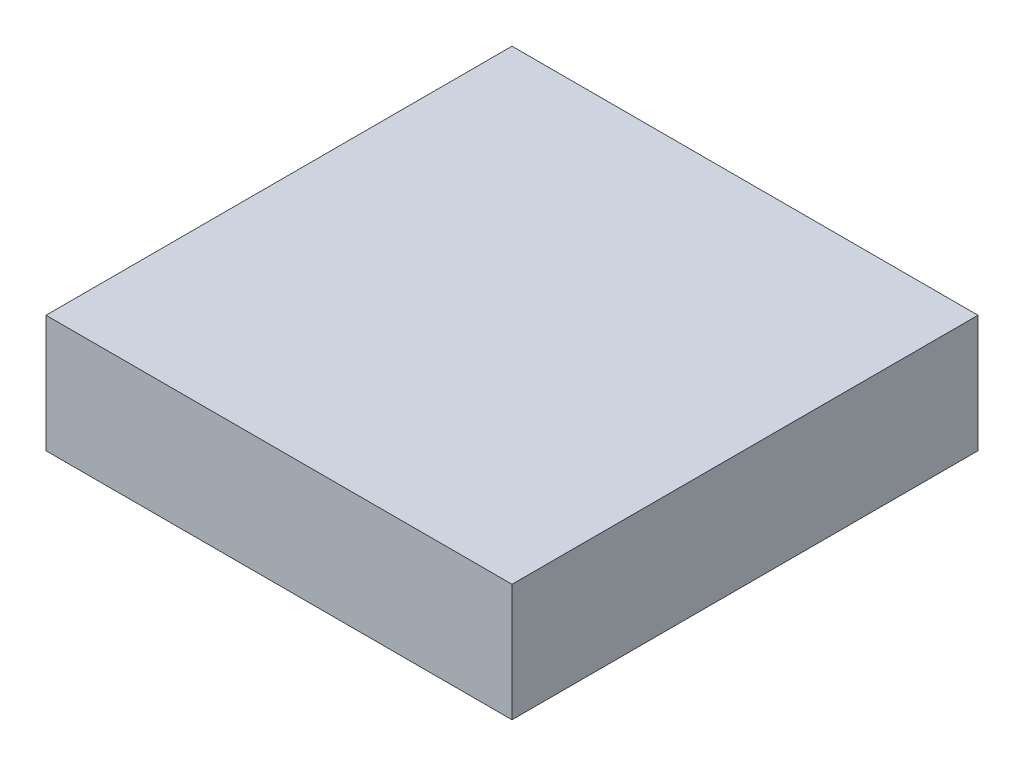
SolidWorks part; units mm, degrees
ref_plane "Front Plane" through (0, 0, 0) normal (0, 0, 1) x (1, 0, 0)
ref_plane "Top Plane" through (0, 0, 0) normal (0, 1, 0) x (1, 0, 0)
ref_plane "Right Plane" through (0, 0, 0) normal (1, 0, 0) x (0, 0, -1)
sketch "Sketch2" plane through (0, 0, 0) normal (0, 1, 0) x (1, 0, 0)
  line L1 (0, 0) -> (170.18, 0)
  line L2 (0, 0) -> (0, 170.18)
  line L3 (0, 170.18) -> (170.18, 170.18)
  line L4 (170.18, 0) -> (170.18, 170.18)
  dimension "D1" = 170.18
  dimension "D2" = 170.18
extrude "Boss-Extrude1" add sketch "Sketch2" along normal blind 42.8625
